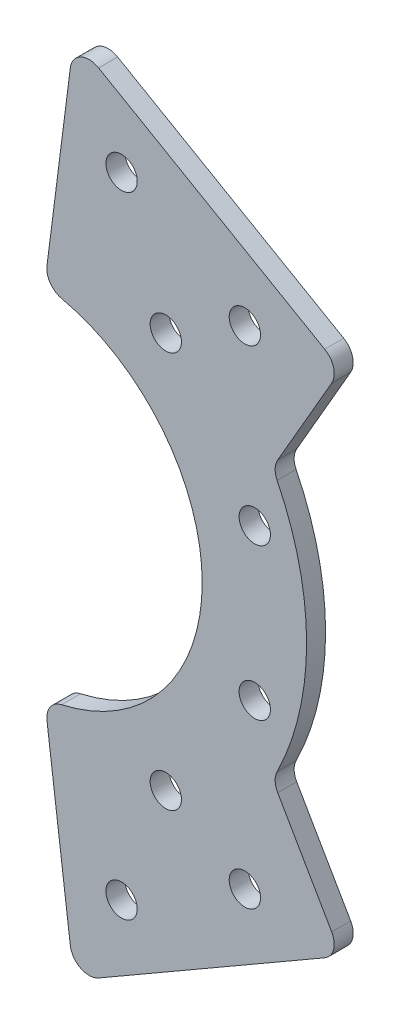
SolidWorks part; units mm, degrees
ref_plane "Front Plane" through (0, 0, 0) normal (0, 0, 1) x (1, 0, 0)
ref_plane "Top Plane" through (0, 0, 0) normal (0, 1, 0) x (1, 0, 0)
ref_plane "Right Plane" through (0, 0, 0) normal (1, 0, 0) x (0, 0, -1)
sketch "Sketch1" plane through (0, 0, 0) normal (0, 0, 1) x (1, 0, 0)
  line L0 (5.2889, 41.4732) -> (10.2119, 80.0766)
  line L2 (38, 0) -> (0, 0) construction
  line L3 (0, 0) -> (34, 58.8897) construction
  line L4 (21.0096, 66.3897) -> (46.9904, 51.3897) construction
  line L5 (34, 58.8897) -> (40, 69.282) construction
  line L7 (5.2889, -41.4732) -> (10.2119, -80.0766)
  line L8 (16.1797, 83.0347) -> (63.8203, 55.5294)
  line L9 (65.2844, 50.0653) -> (53.9085, 30.3617)
  line L10 (65.2844, -50.0653) -> (53.9085, -30.3617)
  line L11 (16.1797, -83.0347) -> (63.8203, -55.5294)
  circle A0 centre (0, 0) radius 51.6 construction
  circle A1 centre (0, 51.6) radius 3.3 construction
  circle A2 centre (30.3297, 41.7453) radius 3.3
  circle A3 centre (49.0745, 15.9453) radius 3.3
  circle A4 centre (49.0745, -15.9453) radius 3.3
  circle A5 centre (30.3297, -41.7453) radius 3.3
  circle A6 centre (0, -51.6) radius 3.3 construction
  circle A7 centre (-30.3297, -41.7453) radius 3.3 construction
  circle A8 centre (-49.0745, -15.9453) radius 3.3 construction
  circle A9 centre (-49.0745, 15.9453) radius 3.3 construction
  circle A10 centre (-30.3297, 41.7453) radius 3.3 construction
  arc A11 (8.3752, 37.0656) -> (8.3752, -37.0656) centre (0, 0) cw
  arc A12 (10.4189, -59.0885) -> (10.4189, 59.0885) centre (0, 0) ccw construction
  circle A13 centre (21.0096, 66.3897) radius 3.3
  circle A14 centre (46.9904, 51.3897) radius 3.3
  arc A20 (8.3752, 37.0656) -> (5.2889, 41.4732) centre (9.2568, 40.9672) cw
  circle A23 centre (46.9904, -51.3897) radius 3.3
  circle A24 centre (21.0096, -66.3897) radius 3.3
  arc A27 (8.3752, -37.0656) -> (5.2889, -41.4732) centre (9.2568, -40.9672) ccw
  arc A28 (10.2119, 80.0766) -> (16.1797, 83.0347) centre (14.1797, 79.5706) cw
  arc A29 (53.7868, 26.5891) -> (53.9085, 30.3617) centre (57.3726, 28.3617) cw
  arc A30 (65.2844, 50.0653) -> (63.8203, 55.5294) centre (61.8203, 52.0653) ccw
  arc A31 (53.7868, -26.5891) -> (53.9085, -30.3617) centre (57.3726, -28.3617) ccw
  arc A32 (65.2844, -50.0653) -> (63.8203, -55.5294) centre (61.8203, -52.0653) cw
  arc A33 (10.2119, -80.0766) -> (16.1797, -83.0347) centre (14.1797, -79.5706) ccw
  arc A34 (53.7868, 26.5891) -> (53.7868, -26.5891) centre (0, 0) cw
  point P6 (60, 0)
  point P25 (0, 0)
  point P28 (38, 0)
  point P35 (34, 58.8897)
  point P42 (40, 69.282)
  point P51 (4.8071, 37.6947)
  dimension "FlangeHoleDiameter" = 103.2
  dimension "M6ClearanceDiameter" = 6.6
  dimension "InnerRadius" = 38
  dimension "OuterRadius" = 60
  dimension "D6" = 4
  dimension "D1" = 4
  dimension "D3" = 4
  dimension "DualBracketSemiAngle" = 60
  dimension "StrutHoleOffsetRadius" = 68
  dimension "StrutHoleSpacing" = 30
  dimension "BracketOuterRadius" = 80
  dimension "FlangeHoleAngle" = 36
  dimension "BracketAngle" = 160
  dimension "D2" = 160
  dimension "FlangeHoleNumber" = 10
extrude "Boss-Extrude1" add sketch "Sketch1" along normal blind 4
equation "\"BracketAngle@Sketch1\"=160"
equation "\"D2@Sketch1\"=\"BracketAngle@Sketch1\""
equation "\"DualBracketSemiAngle@Sketch1\"=360/6"
